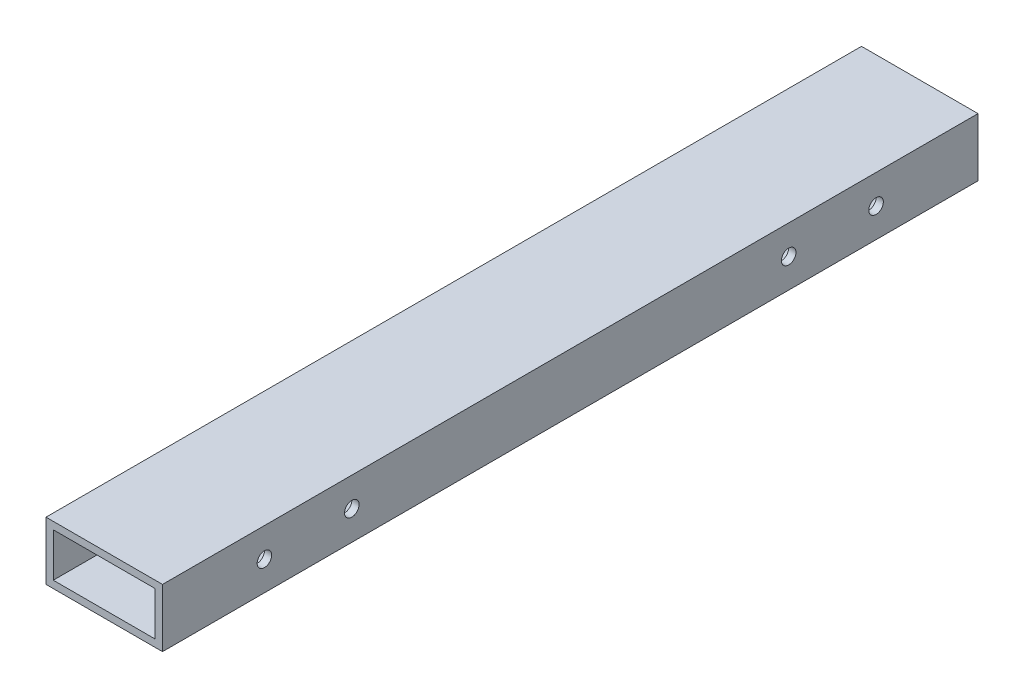
SolidWorks part; units mm, degrees
ref_plane "Front Plane" through (0, 0, 0) normal (0, 0, 1) x (1, 0, 0)
ref_plane "Top Plane" through (0, 0, 0) normal (0, 1, 0) x (1, 0, 0)
ref_plane "Right Plane" through (0, 0, 0) normal (1, 0, 0) x (0, 0, -1)
sketch "Sketch1" plane through (0, 0, 0) normal (0, 0, 1) x (1, 0, 0)
  line L0 (3.175, 22.225) -> (47.625, 22.225)
  line L1 (0, 0) -> (50.8, 0)
  line L2 (0, 0) -> (0, 25.4)
  line L3 (0, 25.4) -> (50.8, 25.4)
  line L4 (50.8, 0) -> (50.8, 25.4)
  line L5 (47.625, 3.175) -> (47.625, 22.225)
  line L6 (3.175, 3.175) -> (47.625, 3.175)
  line L7 (3.175, 3.175) -> (3.175, 22.225)
  dimension "D1" = 25.4
  dimension "D2" = 50.8
  dimension "D3" = 3.175
extrude "Boss-Extrude1" add sketch "Sketch1" along normal blind 355.6
sketch "Sketch2" plane through (50.8, 0, 0) normal (1, 0, 0) x (0, 0, -1)
  line L0 (-177.8, 25.4) -> (-177.8, 12.7) construction
  line L1 (-355.6, 25.4) -> (0, 25.4) construction
  line L2 (-177.8, 12.7) -> (-273.05, 12.7) construction
  line L3 (-273.05, 12.7) -> (-311.15, 12.7) construction
  circle A0 centre (-273.05, 12.7) radius 3.175
  circle A1 centre (-311.15, 12.7) radius 3.175
  circle A2 centre (-44.45, 12.7) radius 3.175
  circle A3 centre (-82.55, 12.7) radius 3.175
  dimension "D4" = 6.35
  dimension "D1" = 12.7
  dimension "D2" = 38.1
  dimension "D3" = 95.25
extrude "Cut-Extrude1" cut sketch "Sketch2" against normal through all both
